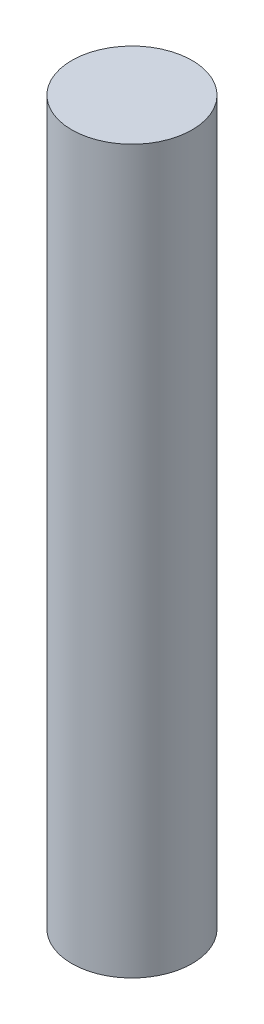
SolidWorks part; units mm, degrees
ref_plane "Front Plane" through (0, 0, 0) normal (0, 0, 1) x (1, 0, 0)
ref_plane "Top Plane" through (0, 0, 0) normal (0, 1, 0) x (1, 0, 0)
ref_plane "Right Plane" through (0, 0, 0) normal (1, 0, 0) x (0, 0, -1)
sketch "Sketch1" plane through (0, 0, 0) normal (0, 1, 0) x (1, 0, 0)
  circle A0 centre (0, 0) radius 2.3813
extrude "Boss-Extrude1" add sketch "Sketch1" along normal blind 28.575
